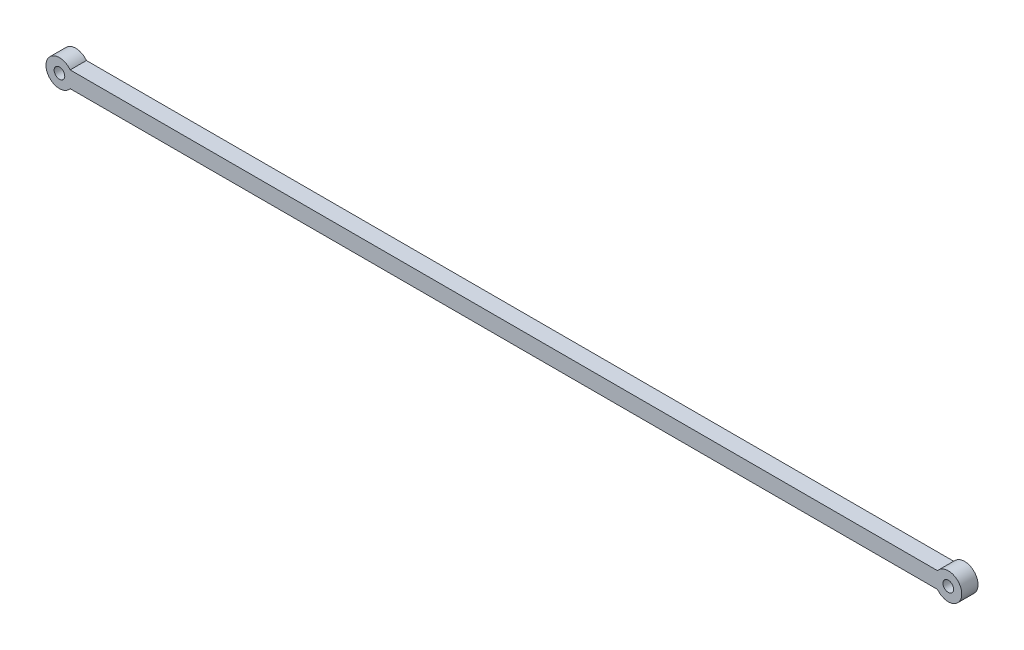
SolidWorks part; units mm, degrees
ref_plane "Front Plane" through (0, 0, 0) normal (0, 0, 1) x (1, 0, 0)
ref_plane "Top Plane" through (0, 0, 0) normal (0, 1, 0) x (1, 0, 0)
ref_plane "Right Plane" through (0, 0, 0) normal (1, 0, 0) x (0, 0, -1)
sketch "Sketch3" plane through (0, 0, 0) normal (0, 0, 1) x (1, 0, 0)
  line L0 (-625.3521, 0) -> (574.6479, 0) construction
  line L2 (-610.8885, 10.9763) -> (560.1843, 10.9763)
  line L3 (-610.8885, 10.9763) -> (-610.8885, -10.9763)
  line L4 (-610.8885, -10.9763) -> (560.1843, -10.9763)
  line L5 (560.1843, 10.9763) -> (560.1843, -10.9763)
  circle A0 centre (-625.3521, 0) radius 18.1569
  circle A1 centre (574.6479, 0) radius 18.1569
  point P9 (0, 0)
  point P10 (0, 0)
  dimension "D2" = 36.3139
  dimension "D1" = 1200
  dimension "D3" = 21.9525
extrude "Boss-Extrude1" add sketch "Sketch3" along normal mid plane 21.9525 contours L2 L5 L4 L3 | A0 | A1
sketch "Sketch4" plane through (0, 0, 10.9763) normal (0, 0, 1) x (1, 0, 0)
  circle A0 centre (-625.3521, 0) radius 7.1807
  circle A1 centre (574.6479, 0) radius 7.1807
  dimension "D1" = 14.3614
extrude "Cut-Extrude1" cut sketch "Sketch4" against normal through all
